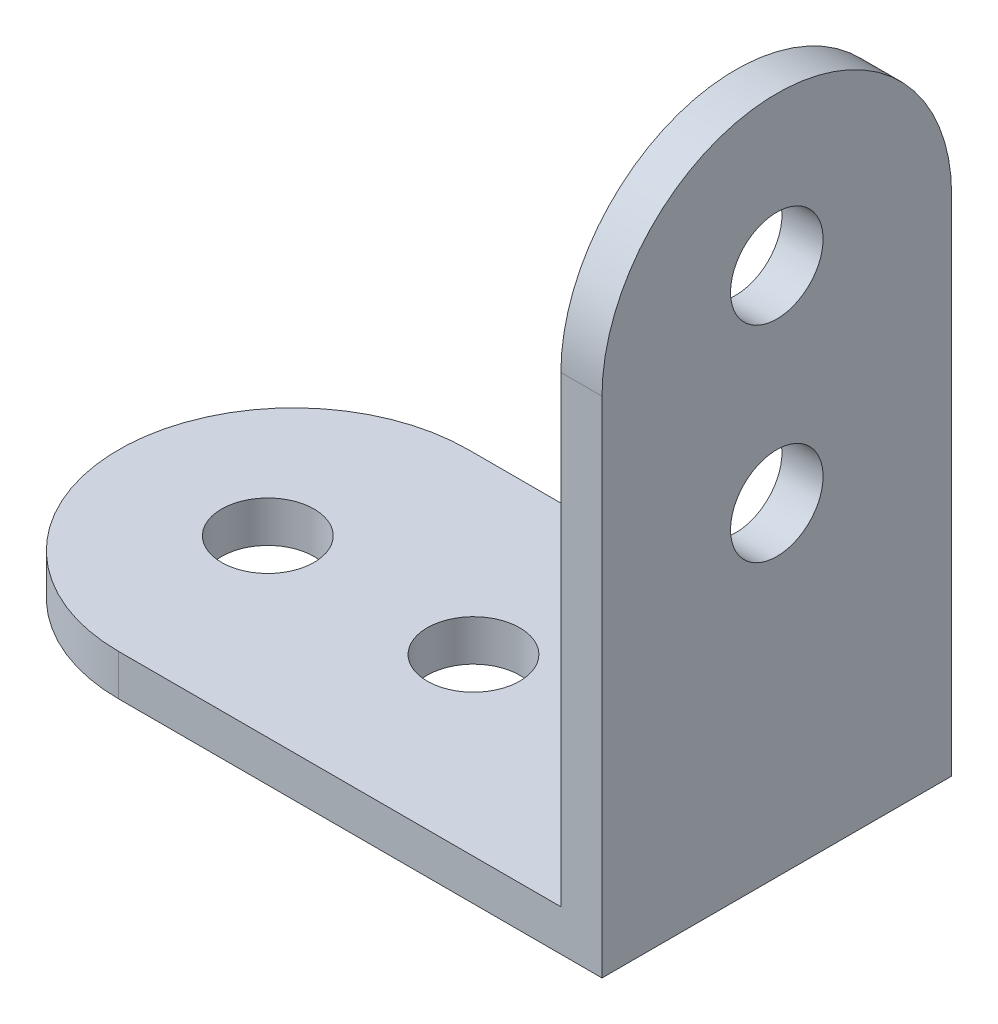
SolidWorks part; units mm, degrees
ref_plane "Front Plane" through (0, 0, 0) normal (0, 0, 1) x (1, 0, 0)
ref_plane "Top Plane" through (0, 0, 0) normal (0, 1, 0) x (1, 0, 0)
ref_plane "Right Plane" through (0, 0, 0) normal (1, 0, 0) x (0, 0, -1)
sketch "Esquisse1" plane through (0, 0, 0) normal (0, 0, 1) x (1, 0, 0)
  line L0 (0, 0) -> (32, 0)
  line L1 (32, 0) -> (32, 33)
  line L2 (32, 33) -> (30, 33)
  line L3 (30, 33) -> (30, 2)
  line L4 (30, 2) -> (0, 2)
  line L5 (0, 2) -> (0, 0)
  dimension "D1" = 32
  dimension "D2" = 33
  dimension "D3" = 2
  dimension "D4" = 2
extrude "Boss.-Extru.1" add sketch "Esquisse1" along normal blind 17
sketch "Esquisse2" plane through (30, 0, 0) normal (-1, 0, 0) x (0, 0, 1)
  line L0 (17, 33) -> (17, 2) construction
  line L1 (0, 24.5) -> (17, 24.5)
  line L2 (17, 33) -> (0, 33) construction
  line L3 (0, 33) -> (17, 33)
  line L4 (17, 33) -> (17, 24.5)
  line L5 (0, 24.5) -> (0, 33)
  arc A0 (17, 24.5) -> (0, 24.5) centre (8.5, 24.5) ccw
  line M1 (0, 33) -> (0, 2)
  line M3 (17, 2) -> (17, 33)
  line M4 (17, 33) -> (0, 33)
  dimension "D1" = 17
  dimension "D2" = 8.5
extrude "Enlèv. mat.-Extru.1" cut sketch "Esquisse2" against normal through all contours A0 M3 M4 | A0 L3 M1
sketch "Esquisse3" plane through (0, 2, 0) normal (0, 1, 0) x (1, 0, 0)
  line L0 (30, 0) -> (0, 0) construction
  line L1 (0, -17) -> (0, 0) construction
  line L6 (30, 0) -> (0, 0)
  line L7 (0, 0) -> (0, -17)
  line L8 (0, -17) -> (30, -17)
  line L9 (30, -17) -> (30, 0)
  line L10 (8.5, 0) -> (0, 0)
  line L11 (0, 0) -> (0, -17)
  line L12 (0, -17) -> (8.5, -17)
  line L13 (30, -17) -> (30, 0)
  arc A0 (8.5, 0) -> (8.5, -17) centre (8.5, -8.5) ccw
  line M5 (30, 0) -> (0, 0)
  line M6 (0, 0) -> (0, -17)
  line M7 (0, -17) -> (30, -17)
  dimension "D1" = 17
  dimension "D3" = 0
  dimension "D2" = 8.5
extrude "Enlèv. mat.-Extru.2" cut sketch "Esquisse3" against normal through all contours A0 L11 M7 | A0 M5 M6
sketch "Esquisse4" plane through (30, 0, 0) normal (-1, 0, 0) x (0, 0, 1)
  circle A0 centre (8.5, 25.75) radius 2.25
  circle A1 centre (8.5, 15.75) radius 2.25
  arc A2 (17, 24.5) -> (0, 24.5) centre (8.5, 24.5) ccw construction
  point P7 (8.5, 33)
  point P8 (0, 0)
  dimension "D1" = 4.5
  dimension "D2" = 7.25
  dimension "D3" = 10
extrude "Enlèv. mat.-Extru.3" cut sketch "Esquisse4" against normal through all
sketch "Esquisse5" plane through (0, 2, 0) normal (0, 1, 0) x (1, 0, 0)
  circle A0 centre (7.25, -8.5) radius 2.25
  circle A1 centre (17.25, -8.5) radius 2.25
  arc A2 (8.5, 0) -> (8.5, -17) centre (8.5, -8.5) ccw construction
  point P7 (0, -8.5)
  dimension "D1" = 4.5
  dimension "D2" = 7.25
  dimension "D3" = 10
extrude "Enlèv. mat.-Extru.4" cut sketch "Esquisse5" against normal through all
